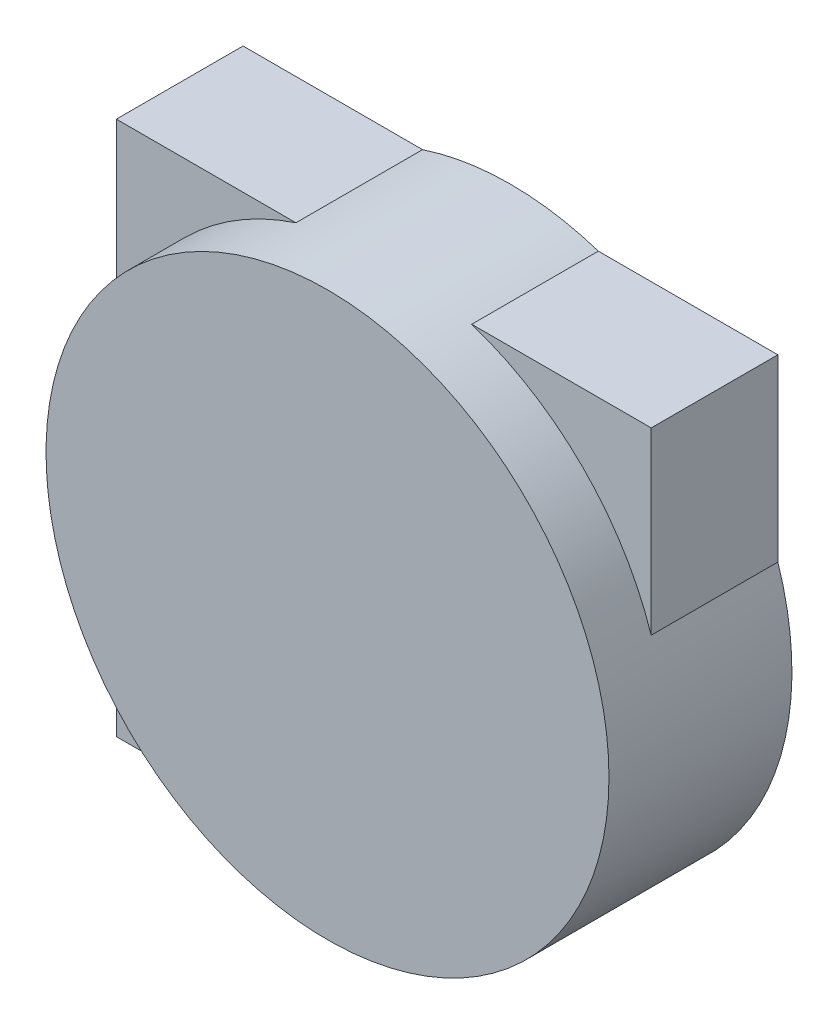
SolidWorks part; units mm, degrees
ref_plane "Front Plane" through (0, 0, 0) normal (0, 0, 1) x (1, 0, 0)
ref_plane "Top Plane" through (0, 0, 0) normal (0, 1, 0) x (1, 0, 0)
ref_plane "Right Plane" through (0, 0, 0) normal (1, 0, 0) x (0, 0, -1)
sketch "Sketch1" plane through (0, 0, 0) normal (0, 0, 1) x (1, 0, 0)
  circle A0 centre (0, 0) radius 20
  dimension "40" = 40
extrude "Boss-Extrude1" add sketch "Sketch1" along normal blind 13
sketch "Sketch2" plane through (0, 0, 0) normal (0, 0, -1) x (-1, 0, 0)
  line L1 (-19, 19) -> (19, 19)
  line L2 (-19, 19) -> (-19, -6.245)
  line L3 (-6.245, -19) -> (19, -19)
  line L4 (19, 19) -> (19, -19)
  arc A0 (-19, -6.245) -> (-6.245, -19) centre (0, 0) ccw
  circle A1 centre (0, 0) radius 20 construction
  point P2 (0, 19)
  point P5 (19, 0)
  dimension "D1" = 38
extrude "Boss-Extrude2" add sketch "Sketch2" against normal blind 9
